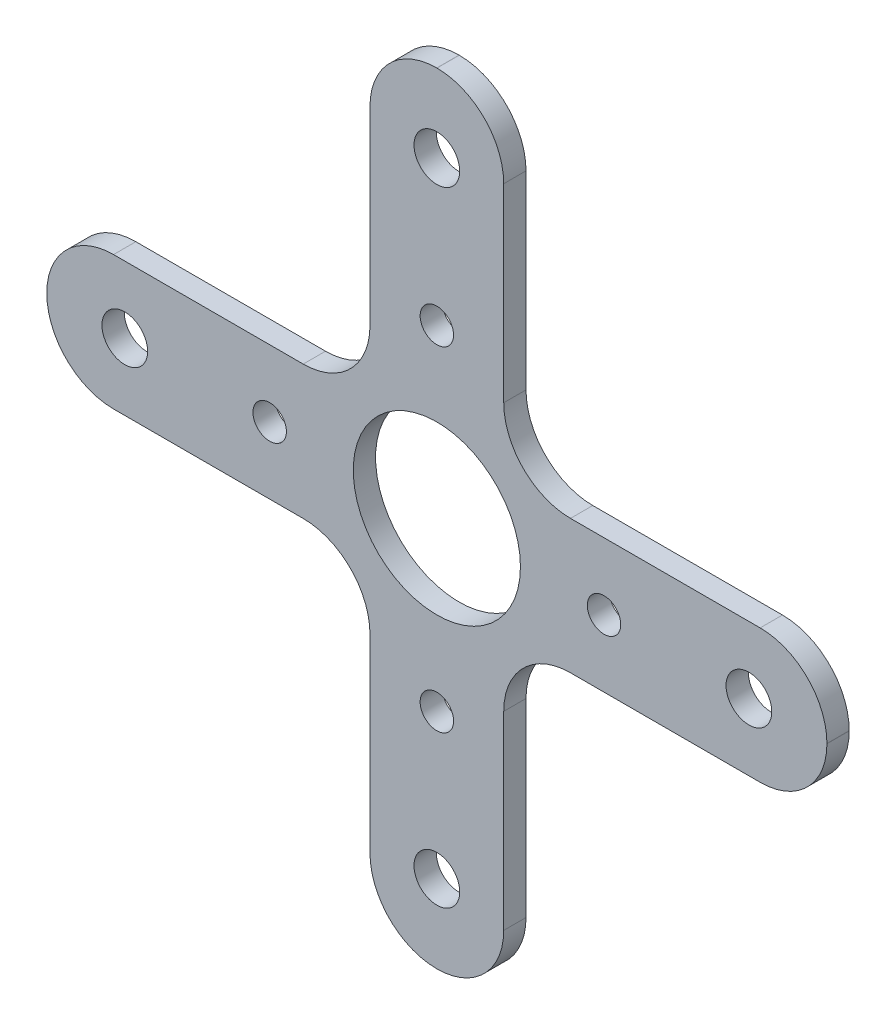
SolidWorks part; units mm, degrees
material "ABS"
ref_plane "Front Plane" through (0, 0, 0) normal (0, 0, 1) x (1, 0, 0)
ref_plane "Top Plane" through (0, 0, 0) normal (0, 1, 0) x (1, 0, 0)
ref_plane "Right Plane" through (0, 0, 0) normal (1, 0, 0) x (0, 0, -1)
sketch "Sketch1" plane through (0, 0, 0) normal (0, 0, 1) x (1, 0, 0)
  line L0 (11.99, -6) -> (29.01, -6)
  line L1 (-29.01, -6) -> (-11.99, -6)
  line L2 (-35, -0.01) -> (-35, 0.01)
  line L3 (-29.01, 6) -> (-11.99, 6)
  line L4 (35, -0.01) -> (35, 0.01)
  line L5 (-35, -6) -> (35, 6) construction
  line L6 (-35, 6) -> (35, -6) construction
  line L7 (-0.01, -35) -> (0.01, -35)
  line L8 (-6, -29.01) -> (-6, -11.99)
  line L9 (-0.01, 35) -> (0.01, 35)
  line L10 (6, -29.01) -> (6, -11.99)
  line L11 (-6, -35) -> (6, 35) construction
  line L12 (-6, 35) -> (6, -35) construction
  line L13 (-6, 11.99) -> (-6, 29.01)
  line L14 (11.99, 6) -> (29.01, 6)
  line L15 (6, 11.99) -> (6, 29.01)
  line L16 (55, 0) -> (-55, 0) construction
  line L17 (0, -55) -> (0, 55) construction
  circle A0 centre (0, 0) radius 7.5
  circle A1 centre (-28, 0) radius 2.05
  circle A2 centre (28, 0) radius 2.05
  circle A3 centre (0, 28) radius 2.05
  circle A4 centre (0, -28) radius 2.05
  arc A5 (-0.01, 35) -> (-6, 29.01) centre (-0.01, 29.01) ccw
  arc A6 (0.01, 35) -> (6, 29.01) centre (0.01, 29.01) cw
  arc A7 (6, -11.99) -> (11.99, -6) centre (11.99, -11.99) cw
  arc A8 (-6, -11.99) -> (-11.99, -6) centre (-11.99, -11.99) ccw
  arc A9 (-11.99, 6) -> (-6, 11.99) centre (-11.99, 11.99) ccw
  arc A10 (11.99, 6) -> (6, 11.99) centre (11.99, 11.99) cw
  arc A11 (29.01, -6) -> (35, -0.01) centre (29.01, -0.01) ccw
  arc A12 (35, 0.01) -> (29.01, 6) centre (29.01, 0.01) ccw
  arc A13 (0.01, -35) -> (6, -29.01) centre (0.01, -29.01) ccw
  arc A14 (-0.01, -35) -> (-6, -29.01) centre (-0.01, -29.01) cw
  arc A15 (-29.01, -6) -> (-35, -0.01) centre (-29.01, -0.01) cw
  arc A16 (-35, 0.01) -> (-29.01, 6) centre (-29.01, 0.01) cw
  circle A17 centre (0, 15) radius 1.5
  circle A18 centre (0, -15) radius 1.5
  circle A19 centre (-15, 0) radius 1.5
  circle A20 centre (15, 0) radius 1.5
  point P0 (0, 0)
  point P6 (0, 0)
  point P37 (6, -6)
  point P42 (-6, 6)
  point P45 (6, 6)
  point P72 (0, 0)
  dimension "D5" = 15
  dimension "D6" = 4.1
  dimension "D8" = 4.1
  dimension "D10" = 5.99
  dimension "D11" = 5.99
  dimension "D12" = 5.99
  dimension "D14" = 3
  dimension "D16" = 3
  dimension "D1" = 70
  dimension "D2" = 70
  dimension "D3" = 12
  dimension "D4" = 12
  dimension "D7" = 28
  dimension "D9" = 28
  dimension "D13" = 15
  dimension "D15" = 15
extrude "Boss-Extrude1" add sketch "Sketch1" along normal blind 2
